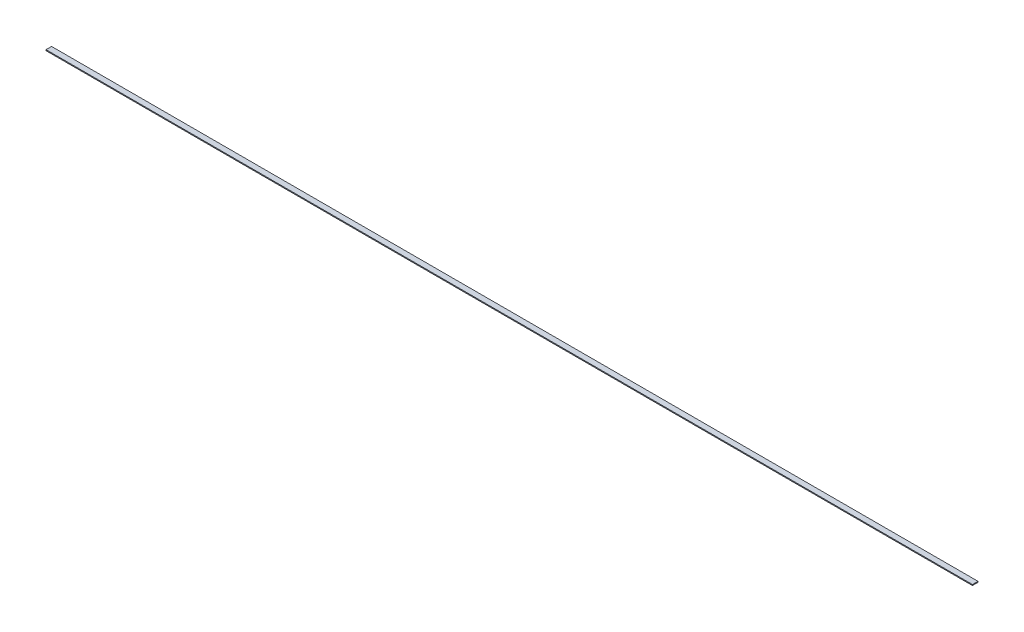
SolidWorks part; units mm, degrees
ref_plane "Front Plane" through (0, 0, 0) normal (0, 0, 1) x (1, 0, 0)
ref_plane "Top Plane" through (0, 0, 0) normal (0, 1, 0) x (1, 0, 0)
ref_plane "Right Plane" through (0, 0, 0) normal (1, 0, 0) x (0, 0, -1)
sketch "Sketch1" plane through (0, 0, 0) normal (0, 0, 1) x (1, 0, 0)
  line L1 (0, 0) -> (1000, 0)
  line L2 (0, 0) -> (0, 1)
  line L3 (0, 1) -> (1000, 1)
  line L4 (1000, 0) -> (1000, 1)
  dimension "D1" = 1
  dimension "D2" = 1000
extrude "Boss-Extrude1" add sketch "Sketch1" along normal blind 6
